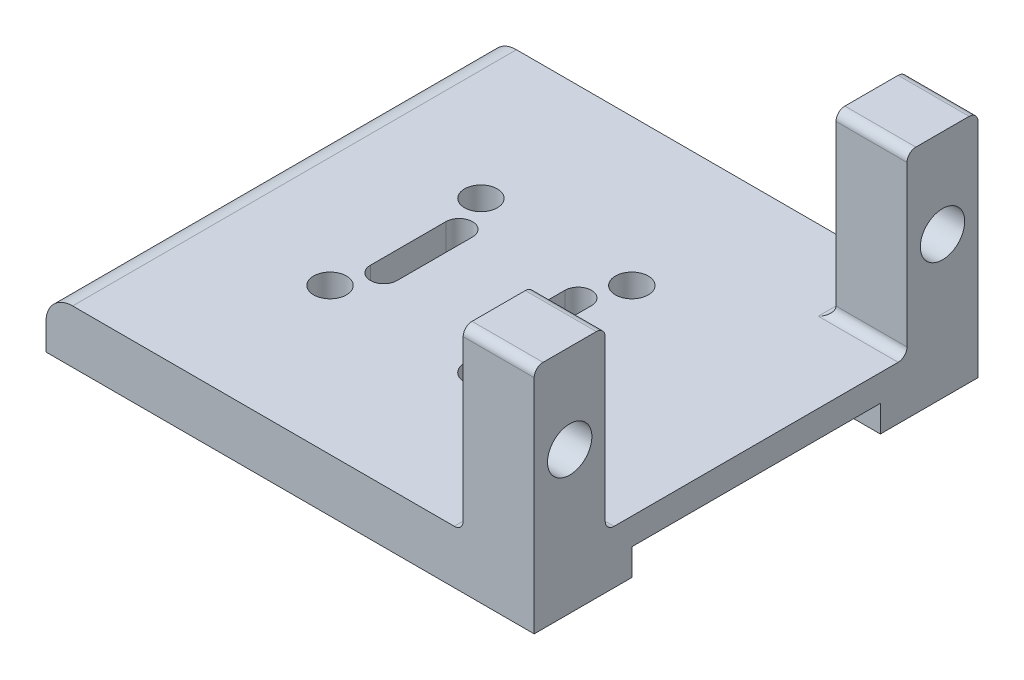
SolidWorks part; units mm, degrees
ref_plane "Front Plane" through (0, 0, 0) normal (0, 0, 1) x (1, 0, 0)
ref_plane "Top Plane" through (0, 0, 0) normal (0, 1, 0) x (1, 0, 0)
ref_plane "Right Plane" through (0, 0, 0) normal (1, 0, 0) x (0, 0, -1)
sketch "Sketch1" plane through (0, 0, 0) normal (0, 1, 0) x (1, 0, 0)
  line L1 (0, 0) -> (60, 0)
  line L2 (0, 0) -> (0, 50)
  line L3 (0, 50) -> (60, 50)
  line L4 (60, 0) -> (60, 50)
  dimension "D1" = 60
  dimension "D2" = 50
extrude "Boss-Extrude1" add sketch "Sketch1" along normal blind 6
sketch "Sketch2" plane through (0, 6, 0) normal (0, 1, 0) x (1, 0, 0)
  line L1 (60, 0) -> (52, 0)
  line L2 (60, 0) -> (60, 8)
  line L3 (60, 8) -> (52, 8)
  line L4 (52, 0) -> (52, 8)
  dimension "D1" = 8
  dimension "D2" = 8
extrude "Boss-Extrude2" add sketch "Sketch2" along normal blind 20
sketch "Sketch3" plane through (60, 0, 0) normal (1, 0, 0) x (0, 0, -1)
  line L0 (0, 26) -> (8, 26) construction
  circle A0 centre (4, 16) radius 2.5
  point P5 (4, 26)
  dimension "D1" = 5
  dimension "D2" = 10
extrude "Cut-Extrude1" cut sketch "Sketch3" against normal up to next
ref_plane "Plane1" through (0, 0, -25) normal (0, 0, 1) x (1, 0, 0)
mirror "Mirror1" about plane through (0, 0, -25) normal (0, 0, 1) of "Cut-Extrude1", "Boss-Extrude2"
sketch "Sketch4" plane through (0, 0, 0) normal (0, -1, 0) x (1, 0, 0)
  line L0 (-1000, -25) -> (49000, -25) construction
  line L1 (0, -50) -> (0, 0) construction
  line L2 (30, -1000) -> (30, 49000) construction
  line L3 (0, 0) -> (60, 0) construction
  line L4 (60, 0) -> (60, -50) construction
  line L5 (15, -39) -> (43, -39)
  line L6 (15, -39) -> (15, -11)
  line L7 (15, -11) -> (43, -11)
  line L8 (43, -39) -> (43, -11)
  line L9 (15, -39) -> (43, -11) construction
  line L10 (15, -11) -> (43, -39) construction
  line L11 (43, -11) -> (60, -11)
  line L12 (43, -11) -> (43, -39)
  line L13 (43, -39) -> (60, -39)
  line L14 (60, -11) -> (60, -39)
  point P5 (0, -25)
  point P6 (30, -25)
  point P10 (30, 0)
  point P12 (29, -25)
  point P20 (0, 0)
  point P21 (0, 0)
  line M7 (60, -50) -> (60, 0)
  dimension "D1" = 28
  dimension "D2" = 28
  dimension "D3" = 1
extrude "Cut-Extrude2" cut sketch "Sketch4" against normal blind 3 contours L5 L8 L7 L6 | L8 L13 L11 M7
sketch "Sketch5" plane through (0, 3, 0) normal (0, -1, 0) x (1, 0, 0)
  line L0 (15, -39) -> (15, -11) construction
  line L1 (40.5, -36.5) -> (17.5, -36.5) construction
  line L2 (40.5, -36.5) -> (40.5, -13.5) construction
  line L3 (40.5, -13.5) -> (17.5, -13.5) construction
  line L4 (17.5, -36.5) -> (17.5, -13.5) construction
  line L5 (40.5, -36.5) -> (17.5, -13.5) construction
  line L6 (40.5, -13.5) -> (17.5, -36.5) construction
  line L7 (37.5, -33.5) -> (20.5, -33.5) construction
  line L8 (37.5, -33.5) -> (37.5, -16.5) construction
  line L9 (37.5, -16.5) -> (20.5, -16.5) construction
  line L10 (20.5, -33.5) -> (20.5, -16.5) construction
  line L11 (37.5, -33.5) -> (20.5, -16.5) construction
  line L12 (37.5, -16.5) -> (20.5, -33.5) construction
  line L13 (15, -39) -> (60, -39) construction
  line L14 (35.7, -20.75) -> (35.7, -29.25) construction
  line L15 (37.2, -20.75) -> (37.2, -29.25)
  line L16 (34.2, -20.75) -> (34.2, -29.25)
  line L17 (22.3, -20.75) -> (22.3, -29.25) construction
  line L18 (23.8, -20.75) -> (23.8, -29.25)
  line L19 (20.8, -20.75) -> (20.8, -29.25)
  line L20 (22.3, -29.25) -> (20.5, -33.5) construction
  line L21 (20.5, -16.5) -> (22.3, -20.75) construction
  line L22 (35.7, -29.25) -> (37.5, -33.5) construction
  line L23 (35.7, -20.75) -> (37.5, -16.5) construction
  circle A0 centre (20.5, -16.5) radius 1.85
  circle A1 centre (37.5, -16.5) radius 1.85
  circle A2 centre (37.5, -33.5) radius 1.85
  circle A3 centre (20.5, -33.5) radius 1.85
  arc A4 (37.2, -20.75) -> (34.2, -20.75) centre (35.7, -20.75) ccw
  arc A5 (34.2, -29.25) -> (37.2, -29.25) centre (35.7, -29.25) ccw
  arc A6 (23.8, -20.75) -> (20.8, -20.75) centre (22.3, -20.75) ccw
  arc A7 (20.8, -29.25) -> (23.8, -29.25) centre (22.3, -29.25) ccw
  point P0 (29, -25)
  point P5 (29, -25)
  point P20 (35.7, -25)
  point P25 (22.3, -25)
  dimension "D7" = 3.7
  dimension "D1" = 23
  dimension "D2" = 23
  dimension "D3" = 17
  dimension "D4" = 17
  dimension "D5" = 2.5
  dimension "D6" = 2.5
  dimension "D8" = 8.5
  dimension "D9" = 1.8
  dimension "D10" = 3
  dimension "D11" = 3
  dimension "D13" = 8.5
  dimension "D14" = 1.8
extrude "Cut-Extrude3" cut sketch "Sketch5" against normal up to next
sketch "Sketch6" plane through (0, 0, 0) normal (-1, 0, 0) x (0, 0, 1)
  line L4 (-50, 0) -> (0, 0)
  line L5 (0, 0) -> (0, 6)
  line L6 (0, 6) -> (-50, 6)
  line L7 (-50, 6) -> (-50, 0)
  line L8 (-50, 0) -> (0, 0)
  line L9 (0, 0) -> (0, 6)
  line L10 (0, 6) -> (-50, 6)
  line L11 (-50, 6) -> (-50, 0)
  dimension "D1" = 0
extrude "Cut-Extrude4" cut sketch "Sketch6" against normal blind 5
fillet "Fillet1" radius 1 4 edges at (56, 26, 0) (56, 26, -42) (56, 26, -8) (56, 26, -50)
fillet "Fillet2" radius 1 4 edges at (52, 6, -4) (52, 6, -46) (56, 6, -42) (56, 6, -8)
fillet "Fillet4" radius 3 1 edges at (5, 6, -25)
